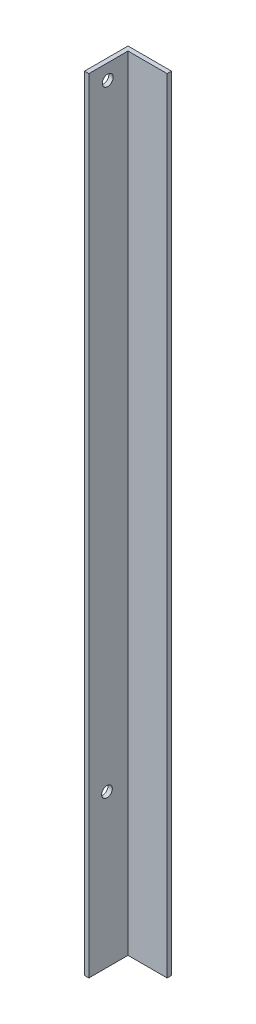
SolidWorks part; units mm, degrees
material "6061 Alloy"
ref_plane "Front Plane" through (0, 0, 0) normal (0, 0, 1) x (1, 0, 0)
ref_plane "Top Plane" through (0, 0, 0) normal (0, 1, 0) x (1, 0, 0)
ref_plane "Right Plane" through (0, 0, 0) normal (1, 0, 0) x (0, 0, -1)
sketch "Sketch1" plane through (0, 0, 0) normal (0, 1, 0) x (1, 0, 0)
  line L0 (-24.9936, -7.8232) -> (-24.9936, 17.5768)
  line L1 (-24.9936, 17.5768) -> (0.4064, 17.5768)
  dimension "D1" = 25.4
  dimension "D2" = 25.4
extrude "Extrude-Thin1" add sketch "Sketch1" along normal blind 457.2 thin
sketch "Sketch3" plane through (-22.4536, 0, 0) normal (1, 0, 0) x (0, 0, -1)
  line L0 (-7.8232, 457.2) -> (15.0368, 457.2) construction
  circle A0 centre (3.2058, 448.31) radius 3.175
  dimension "D1" = 8.89
  dimension "D2" = 6.35
extrude "Cut-Extrude1" cut sketch "Sketch3" against normal through all
sketch "Sketch4" plane through (-22.4536, 0, 0) normal (1, 0, 0) x (0, 0, -1)
  line L0 (-7.8232, 0) -> (15.0368, 0) construction
  circle A0 centre (2.7618, 88.9) radius 3.1119
  dimension "D1" = 88.9
extrude "Cut-Extrude2" cut sketch "Sketch4" against normal through all
